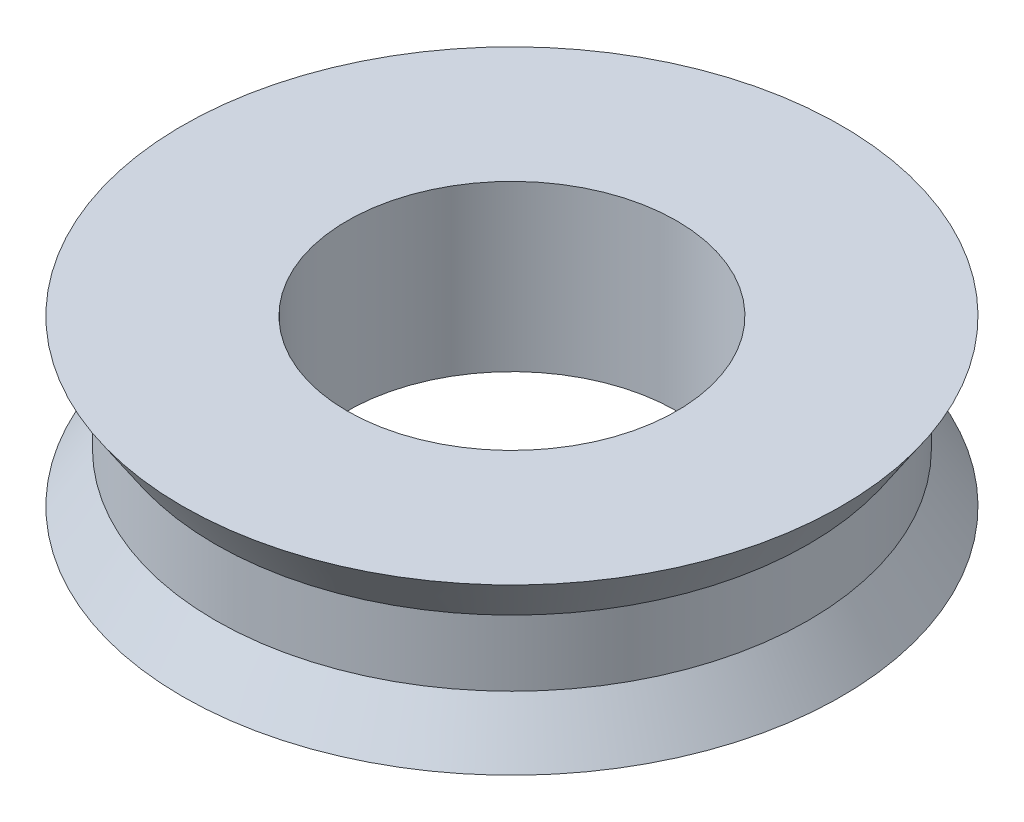
SolidWorks part; units mm, degrees
ref_plane "Front Plane" through (0, 0, 0) normal (0, 0, 1) x (1, 0, 0)
ref_plane "Top Plane" through (0, 0, 0) normal (0, 1, 0) x (1, 0, 0)
ref_plane "Right Plane" through (0, 0, 0) normal (1, 0, 0) x (0, 0, -1)
sketch "Sketch1" plane through (0, 0, 0) normal (0, 0, 1) x (1, 0, 0)
  line L0 (0, 0) -> (-6.35, 0)
  line L1 (-6.35, 0) -> (-6.35, 6.35)
  line L2 (-6.35, 6.35) -> (0, 6.35)
  line L3 (0, 6.35) -> (0, 0)
  line L4 (-6.35, 6.35) -> (-12.7, 6.35)
  line L5 (-6.35, 3.175) -> (-11.43, 3.175)
  line L6 (-11.43, 1.905) -> (-11.43, 4.445)
  line L7 (-12.7, 0) -> (-6.35, 0)
  line L8 (-11.43, 4.445) -> (-12.7, 6.35)
  line L9 (-11.43, 1.905) -> (-12.7, 0)
  dimension "D1" = 6.35
  dimension "D2" = 6.35
  dimension "D3" = 6.35
  dimension "D4" = 5.08
  dimension "D5" = 2.54
revolve "Revolve1" add sketch "Sketch1" angle 360 about L3
